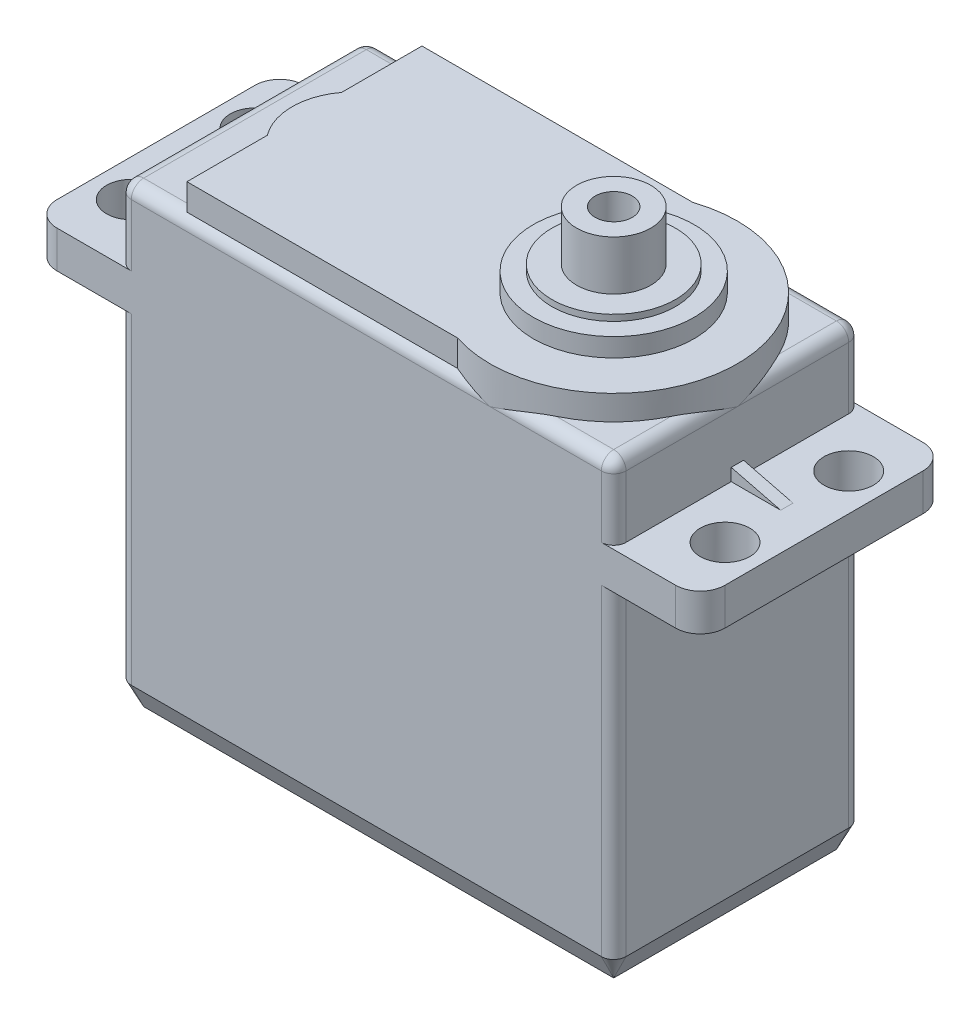
SolidWorks part; units mm, degrees
ref_plane "前视基准面" through (0, 0, 0) normal (0, 0, 1) x (1, 0, 0)
ref_plane "上视基准面" through (0, 0, 0) normal (0, 1, 0) x (1, 0, 0)
ref_plane "右视基准面" through (0, 0, 0) normal (1, 0, 0) x (0, 0, -1)
sketch "草图1" plane through (0, 0, 0) normal (0, 1, 0) x (1, 0, 0)
  line L1 (-27, 10) -> (27, 10)
  line L2 (-27, 10) -> (-27, -10)
  line L3 (-27, -10) -> (27, -10)
  line L4 (27, 10) -> (27, -10)
  line L5 (-27, 10) -> (27, -10) construction
  line L6 (-27, -10) -> (27, 10) construction
  point P0 (0, 0)
  dimension "D1" = 54
  dimension "D2" = 20
extrude "凸台-拉伸1" add sketch "草图1" along normal blind 37
sketch "草图2" plane through (0, 0, 0) normal (0, -1, 0) x (1, 0, 0)
  line L1 (-20, 10) -> (20, 10)
  line L2 (-20, 10) -> (-20, -10)
  line L3 (-20, -10) -> (20, -10)
  line L4 (20, 10) -> (20, -10)
  line L5 (-20, 10) -> (20, -10) construction
  line L6 (-20, -10) -> (20, 10) construction
  line L7 (-33.9613, 19.7038) -> (33.9613, 19.7038)
  line L8 (-33.9613, 19.7038) -> (-33.9613, -19.7038)
  line L9 (-33.9613, -19.7038) -> (33.9613, -19.7038)
  line L10 (33.9613, 19.7038) -> (33.9613, -19.7038)
  line L11 (-33.9613, 19.7038) -> (33.9613, -19.7038) construction
  line L12 (-33.9613, -19.7038) -> (33.9613, 19.7038) construction
  point P0 (0, 0)
  point P6 (0, 0)
  dimension "D1" = 40
  dimension "D2" = 20
extrude "切除-拉伸1" cut sketch "草图2" against normal blind 28
sketch "草图3" plane through (0, 37, 0) normal (0, 1, 0) x (1, 0, 0)
  line L1 (-20, 10) -> (20, 10)
  line L2 (-20, 10) -> (-20, -10)
  line L3 (-20, -10) -> (20, -10)
  line L4 (20, 10) -> (20, -10)
  line L5 (-20, 10) -> (20, -10) construction
  line L6 (-20, -10) -> (20, 10) construction
  line L7 (-33.9613, 16.6929) -> (33.9613, 16.6929)
  line L8 (-33.9613, 16.6929) -> (-33.9613, -16.6929)
  line L9 (-33.9613, -16.6929) -> (33.9613, -16.6929)
  line L10 (33.9613, 16.6929) -> (33.9613, -16.6929)
  line L11 (-33.9613, 16.6929) -> (33.9613, -16.6929) construction
  line L12 (-33.9613, -16.6929) -> (33.9613, 16.6929) construction
  point P0 (0, 0)
  point P6 (0, 0)
  dimension "D1" = 40
  dimension "D2" = 20
extrude "切除-拉伸2" cut sketch "草图3" against normal blind 6
fillet "圆角1" radius 1 12 edges at (20, 34, 10) (20, 34, -10) (-20, 34, 10) (-20, 34, -10) (-20, 14, -10) (20, 14, -10) (20, 14, 10) (-20, 14, 10) (20, 37, 0) (0, 37, -10) (-20, 37, 0) (0, 37, 10)
fillet "圆角2" radius 2 4 edges at (-27, 29.5, -10) (27, 29.5, -10) (-27, 29.5, 10) (27, 29.5, 10)
chamfer "倒角1" distance 1 distance2 2 8 edges at (0, 0, -10) (-19.7071, 0, -9.7071) (19.7071, 0, -9.7071) (-20, 0, 0) (20, 0, 0) (-19.7071, 0, 9.7071) (19.7071, 0, 9.7071) (0, 0, 10)
sketch "草图4" plane through (0, 37, 0) normal (0, 1, 0) x (1, 0, 0)
  line L0 (-36.3246, 0) -> (42.4452, 0) construction
  line L1 (0, 18.5837) -> (0, -20.5352) construction
  circle A0 centre (-24, 5) radius 2
  circle A1 centre (-24, -5) radius 2
  circle A2 centre (24, -5) radius 2
  circle A3 centre (24, 5) radius 2
  dimension "D4" = 4
  dimension "D5" = 4
  dimension "D1" = 5
  dimension "D2" = 5
  dimension "D3" = 24
extrude "切除-拉伸3" cut sketch "草图4" against normal blind 30
sketch "草图5" plane through (0, 0, 0) normal (0, 0, 1) x (1, 0, 0)
  line L0 (-20, 32) -> (-24, 31)
  line L1 (-20, 31) -> (-20, 36) construction
  line L2 (-25, 31) -> (-19, 31) construction
  dimension "D1" = 1
  dimension "D2" = 4
rib "筋1" sketch "草图5" sketch "草图5" thickness 1 extrusion direction parallel to sketch draft on no parameters "D1"=1
mirror "镜向1" about plane through (0, 0, 0) normal (1, 0, 0) of "筋1"
sketch "草图6" plane through (0, 37, 0) normal (0, 1, 0) x (1, 0, 0)
  point P2 (0, 0)
sketch "草图8" plane through (0, 37, 0) normal (0, 1, 0) x (1, 0, 0)
  line L0 (27, -8) -> (27, 8) construction
  line L1 (-15, 9.5) -> (6.8775, 9.5)
  line L2 (-15, 9.5) -> (-15, 3)
  line L3 (-15, -9.5) -> (6.8775, -9.5)
  line L4 (-15, -3) -> (-15, -9.5)
  line L5 (-15, 9.5) -> (15, -9.5) construction
  line L6 (-15, -9.5) -> (15, 9.5) construction
  arc A0 (6.8775, -9.5) -> (6.8775, 9.5) centre (10, 0) ccw
  arc A1 (-15, 3) -> (-15, -3) centre (-11, 0) ccw
  point P2 (0, 0)
  dimension "D2" = 20
  dimension "D1" = 17
  dimension "D3" = 19
  dimension "D4" = 30
extrude "凸台-拉伸4" add sketch "草图8" along normal blind 2 and the other way up to next
sketch "草图9" plane through (0, 39, 0) normal (0, 1, 0) x (1, 0, 0)
  line L0 (27, -8) -> (27, 8) construction
  circle A0 centre (10, 0) radius 6.5
  dimension "D1" = 17
  dimension "D2" = 13
extrude "凸台-拉伸5" add sketch "草图9" along normal blind 2
sketch "草图10" plane through (0, 41, 0) normal (0, 1, 0) x (1, 0, 0)
  circle A0 centre (10, 0) radius 6.5
  circle A1 centre (10, 0) radius 5
  dimension "D1" = 13
  dimension "D2" = 10
extrude "切除-拉伸4" cut sketch "草图10" against normal blind 0.5
sketch "草图11" plane through (0, 41, 0) normal (0, 1, 0) x (1, 0, 0)
  circle A0 centre (10, 0) radius 3
  dimension "D1" = 6
extrude "凸台-拉伸6" add sketch "草图11" along normal blind 4
sketch "草图14" plane through (0, 45, 0) normal (0, 1, 0) x (1, 0, 0)
  circle A0 centre (10, 0) radius 1.5
  dimension "D1" = 3
extrude "切除-拉伸5" cut sketch "草图14" against normal blind 4
scale "缩放比例1" scale about centroid uniform scaling yes scale factor 0.5
